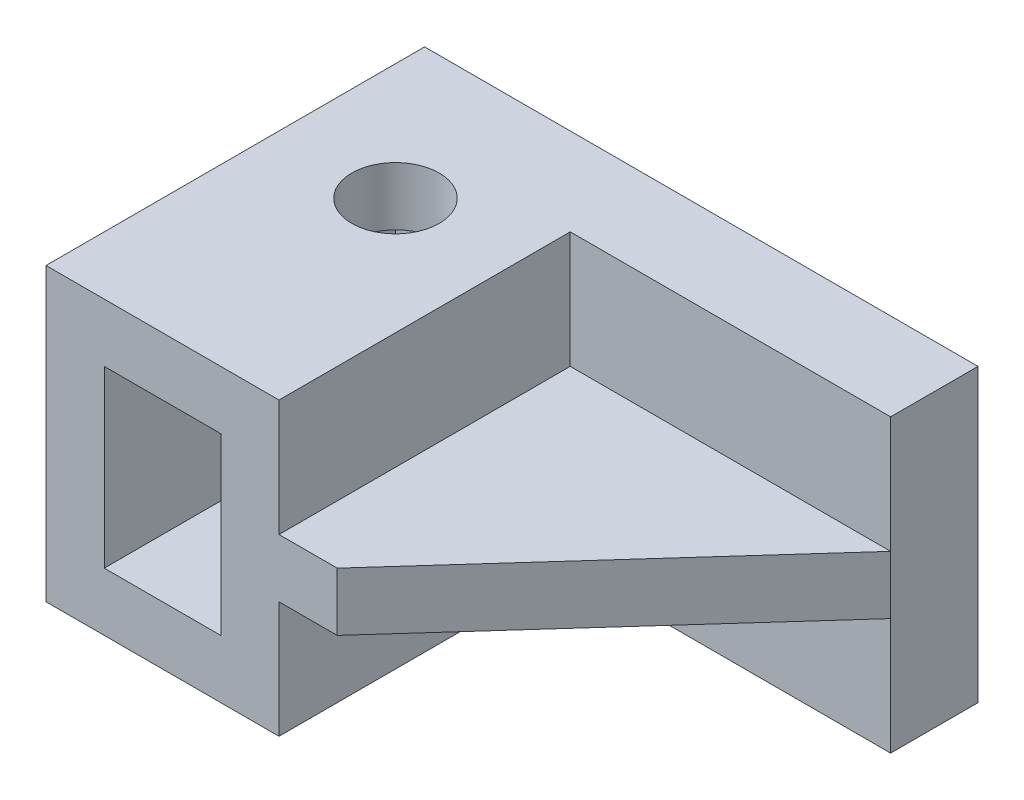
SolidWorks part; units mm, degrees
ref_plane "Front Plane" through (0, 0, 0) normal (0, 0, 1) x (1, 0, 0)
ref_plane "Top Plane" through (0, 0, 0) normal (0, 1, 0) x (1, 0, 0)
ref_plane "Right Plane" through (0, 0, 0) normal (1, 0, 0) x (0, 0, -1)
sketch "Sketch1" plane through (0, 0, 0) normal (0, 0, 1) x (1, 0, 0)
  line L0 (0, 0) -> (2413, 0)
  line L1 (2413, 0) -> (2413, 1270)
  line L2 (2413, 1270) -> (0, 1270)
  line L3 (0, 1270) -> (0, 0)
extrude "Boss-Extrude1" add sketch "Sketch1" along normal blind 381
sketch "Sketch2" plane through (0, 0, 381) normal (0, 0, 1) x (1, 0, 0)
  line L0 (2413, 1270) -> (0, 1270) construction
  line L1 (0, 0) -> (1016, 0)
  line L2 (0, 0) -> (0, 1270)
  line L3 (0, 1270) -> (1016, 1270)
  line L4 (1016, 0) -> (1016, 1270)
extrude "Boss-Extrude2" add sketch "Sketch2" along normal blind 1270
sketch "Sketch3" plane through (0, 0, 1651) normal (0, 0, 1) x (1, 0, 0)
  line L4 (254, 1016) -> (762, 1016)
  line L5 (254, 1016) -> (254, 254)
  line L6 (254, 254) -> (762, 254)
  line L7 (762, 1016) -> (762, 254)
  dimension "D1" = 762
  dimension "D2" = 508
extrude "Cut-Extrude1" cut sketch "Sketch3" against normal blind 1270
sketch "Sketch5" plane through (0, 0, 1651) normal (0, 0, 1) x (1, 0, 0)
  line L0 (1016, 762) -> (1016, 508)
  line L1 (1016, 0) -> (1016, 1270) construction
  line L2 (1016, 762) -> (1270, 762)
  line L3 (1270, 762) -> (1270, 508)
  line L4 (1270, 508) -> (1016, 508)
extrude "Boss-Extrude3" add sketch "Sketch5" against normal blind 1270
sketch "Sketch7" plane through (0, 508, 0) normal (0, -1, 0) x (1, 0, 0)
  line L0 (1270, 1651) -> (2413, 381)
  line L1 (1270, 1651) -> (1270, 381)
  line L2 (1270, 381) -> (2413, 381)
extrude "Boss-Extrude4" add sketch "Sketch7" against normal blind 254
sketch "Sketch8" plane through (0, 0, 0) normal (0, -1, 0) x (1, 0, 0)
  circle A0 centre (508, 635) radius 190.5
extrude "Cut-Extrude2" cut sketch "Sketch8" against normal through all and the other way through all
